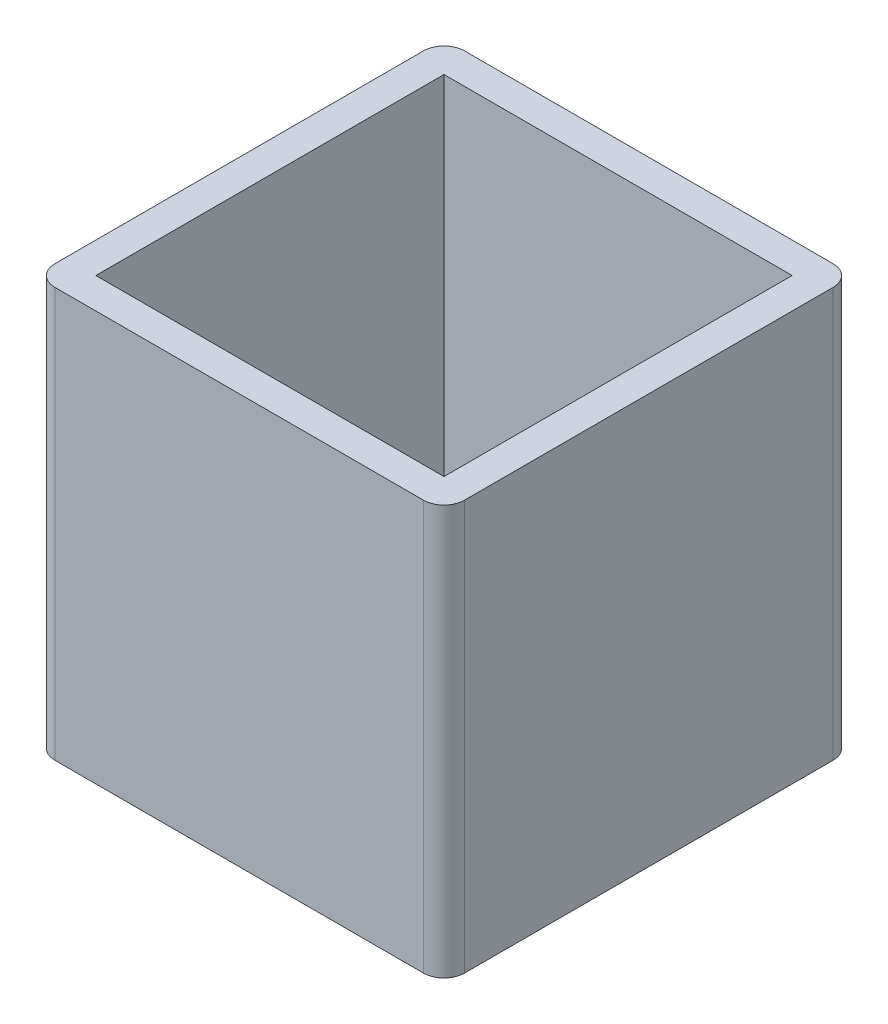
SolidWorks part; units mm, degrees
ref_plane "前视基准面" through (0, 0, 0) normal (0, 0, 1) x (1, 0, 0)
ref_plane "上视基准面" through (0, 0, 0) normal (0, 1, 0) x (1, 0, 0)
ref_plane "右视基准面" through (0, 0, 0) normal (1, 0, 0) x (0, 0, -1)
sketch "草图1" plane through (0, 0, 0) normal (0, 1, 0) x (1, 0, 0)
  line L1 (0, 0) -> (40, 0)
  line L2 (0, 0) -> (0, -40)
  line L3 (0, -40) -> (40, -40)
  line L4 (40, 0) -> (40, -40)
  dimension "D1" = 40
  dimension "D2" = 40
extrude "凸台-拉伸1" add sketch "草图1" along normal blind 40
sketch "草图2" plane through (0, 40, 0) normal (0, 1, 0) x (1, 0, 0)
  line L0 (3, -3) -> (3, -37)
  line L1 (0, 0) -> (40, 0)
  line L2 (0, 0) -> (0, -40)
  line L3 (0, -40) -> (40, -40)
  line L4 (40, 0) -> (40, -40)
  line L5 (3, -37) -> (37, -37)
  line L6 (37, -3) -> (37, -37)
  line L7 (3, -3) -> (37, -3)
  dimension "D1" = 3
extrude "切除-拉伸1" cut sketch "草图2" against normal blind 37 contours L0 L5 L6 L7
fillet "圆角1" radius 2 4 edges at (0, 20, 0) (0, 20, 40) (40, 20, 40) (40, 20, 0)
